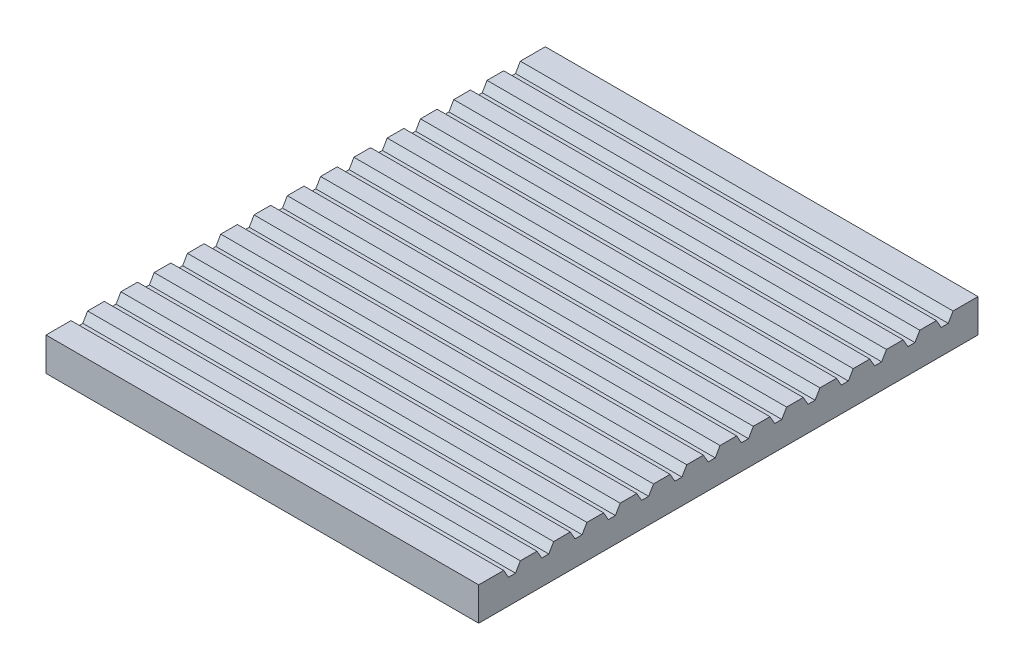
SolidWorks part; units mm, degrees
ref_plane "Front Plane" through (0, 0, 0) normal (0, 0, 1) x (1, 0, 0)
ref_plane "Top Plane" through (0, 0, 0) normal (0, 1, 0) x (1, 0, 0)
ref_plane "Right Plane" through (0, 0, 0) normal (1, 0, 0) x (0, 0, -1)
sketch "Sketch2" plane through (0, 0, 0) normal (0, 1, 0) x (1, 0, 0)
  line L1 (0, -381) -> (330.2, -381)
  line L2 (0, -381) -> (0, 0)
  line L3 (0, 0) -> (330.2, 0)
  line L4 (330.2, -381) -> (330.2, 0)
  point P4 (0, 0)
  dimension "D1" = 330.2
  dimension "D2" = 381
extrude "Boss-Extrude1" add sketch "Sketch2" along normal blind 25.4
sketch "Sketch3" plane through (330.2, 0, 0) normal (1, 0, 0) x (0, 0, -1)
  line L0 (-361.95, 25.4) -> (-358.2838, 19.05)
  line L1 (-381, 25.4) -> (0, 25.4) construction
  line L2 (-358.2838, 19.05) -> (-352.9162, 19.05)
  line L3 (-352.9162, 19.05) -> (-349.25, 25.4)
  line L4 (-349.25, 25.4) -> (-361.95, 25.4)
  line L49 (-323.85, 25.4) -> (-336.55, 25.4)
  line L50 (-336.55, 25.4) -> (-332.8838, 19.05)
  line L51 (-332.8838, 19.05) -> (-327.5162, 19.05)
  line L52 (-327.5162, 19.05) -> (-323.85, 25.4)
  line L53 (-298.45, 25.4) -> (-311.15, 25.4)
  line L54 (-311.15, 25.4) -> (-307.4838, 19.05)
  line L55 (-307.4838, 19.05) -> (-302.1162, 19.05)
  line L56 (-302.1162, 19.05) -> (-298.45, 25.4)
  line L57 (-273.05, 25.4) -> (-285.75, 25.4)
  line L58 (-285.75, 25.4) -> (-282.0838, 19.05)
  line L59 (-282.0838, 19.05) -> (-276.7162, 19.05)
  line L60 (-276.7162, 19.05) -> (-273.05, 25.4)
  line L61 (-247.65, 25.4) -> (-260.35, 25.4)
  line L62 (-260.35, 25.4) -> (-256.6838, 19.05)
  line L63 (-256.6838, 19.05) -> (-251.3162, 19.05)
  line L64 (-251.3162, 19.05) -> (-247.65, 25.4)
  line L65 (-222.25, 25.4) -> (-234.95, 25.4)
  line L66 (-234.95, 25.4) -> (-231.2838, 19.05)
  line L67 (-231.2838, 19.05) -> (-225.9162, 19.05)
  line L68 (-225.9162, 19.05) -> (-222.25, 25.4)
  line L69 (-196.85, 25.4) -> (-209.55, 25.4)
  line L70 (-209.55, 25.4) -> (-205.8838, 19.05)
  line L71 (-205.8838, 19.05) -> (-200.5162, 19.05)
  line L72 (-200.5162, 19.05) -> (-196.85, 25.4)
  line L73 (-171.45, 25.4) -> (-184.15, 25.4)
  line L74 (-184.15, 25.4) -> (-180.4838, 19.05)
  line L75 (-180.4838, 19.05) -> (-175.1162, 19.05)
  line L76 (-175.1162, 19.05) -> (-171.45, 25.4)
  line L77 (-146.05, 25.4) -> (-158.75, 25.4)
  line L78 (-158.75, 25.4) -> (-155.0838, 19.05)
  line L79 (-155.0838, 19.05) -> (-149.7162, 19.05)
  line L80 (-149.7162, 19.05) -> (-146.05, 25.4)
  line L81 (-120.65, 25.4) -> (-133.35, 25.4)
  line L82 (-133.35, 25.4) -> (-129.6838, 19.05)
  line L83 (-129.6838, 19.05) -> (-124.3162, 19.05)
  line L84 (-124.3162, 19.05) -> (-120.65, 25.4)
  line L85 (-95.25, 25.4) -> (-107.95, 25.4)
  line L86 (-107.95, 25.4) -> (-104.2838, 19.05)
  line L87 (-104.2838, 19.05) -> (-98.9162, 19.05)
  line L88 (-98.9162, 19.05) -> (-95.25, 25.4)
  line L89 (-69.85, 25.4) -> (-82.55, 25.4)
  line L90 (-82.55, 25.4) -> (-78.8838, 19.05)
  line L91 (-78.8838, 19.05) -> (-73.5162, 19.05)
  line L92 (-73.5162, 19.05) -> (-69.85, 25.4)
  line L93 (-44.45, 25.4) -> (-57.15, 25.4)
  line L94 (-57.15, 25.4) -> (-53.4838, 19.05)
  line L95 (-53.4838, 19.05) -> (-48.1162, 19.05)
  line L96 (-48.1162, 19.05) -> (-44.45, 25.4)
  line L97 (-19.05, 25.4) -> (-31.75, 25.4)
  line L98 (-31.75, 25.4) -> (-28.0838, 19.05)
  line L99 (-28.0838, 19.05) -> (-22.7162, 19.05)
  line L100 (-22.7162, 19.05) -> (-19.05, 25.4)
  dimension "D1" = 60
  dimension "D2" = 12.7
  dimension "D3" = 6.35
  dimension "D4" = 19.05
extrude "Cut-Extrude1" cut sketch "Sketch3" against normal through all
